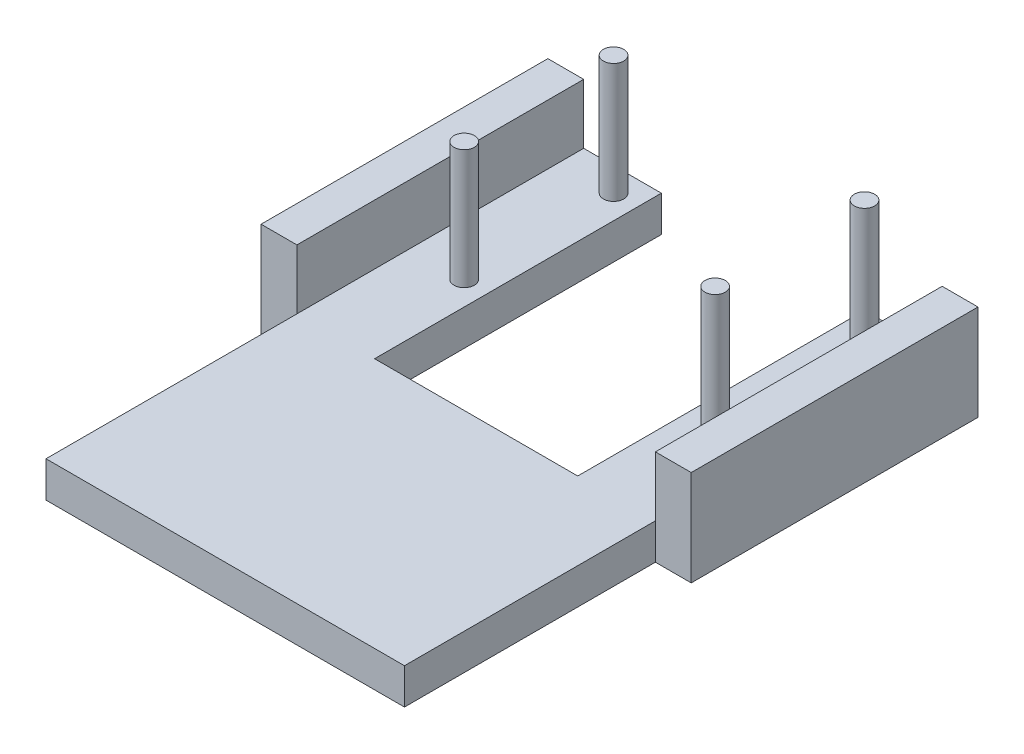
SolidWorks part; units mm, degrees
ref_plane "Front Plane" through (0, 0, 0) normal (0, 0, 1) x (1, 0, 0)
ref_plane "Top Plane" through (0, 0, 0) normal (0, 1, 0) x (1, 0, 0)
ref_plane "Right Plane" through (0, 0, 0) normal (1, 0, 0) x (0, 0, -1)
sketch "Sketch1" plane through (0, 0, 0) normal (0, 1, 0) x (1, 0, 0)
  line L0 (30, 0) -> (0, 0)
  line L17 (30, 0) -> (30, 21)
  line L18 (30, 21) -> (33, 21)
  line L19 (33, 21) -> (33, 45)
  line L20 (-3, 45) -> (6.5, 45)
  line L21 (-3, 45) -> (-3, 21)
  line L22 (-3, 21) -> (0, 21)
  line L23 (0, 21) -> (0, 0)
  line L24 (6.5, 45) -> (6.5, 21)
  line L25 (6.5, 21) -> (23.5, 21)
  line L26 (23.5, 21) -> (23.5, 45)
  line L27 (23.5, 45) -> (33, 45)
  dimension "D1" = 45
  dimension "D2" = 3
  dimension "D3" = 24
  dimension "D4" = 36
  dimension "D5" = 24
  dimension "D6" = 3
  dimension "D7" = 9.5
  dimension "D8" = 9.5
  dimension "D21" = 17
  dimension "D22" = 24
extrude "Boss-Extrude1" add sketch "Sketch1" along normal blind 3
sketch "Sketch2" plane through (0, 3, 0) normal (0, 1, 0) x (1, 0, 0)
  line L0 (0, 21) -> (0, 45)
  line L2 (0, 45) -> (-3, 45)
  line L3 (-3, 45) -> (-3, 21)
  line L4 (-3, 21) -> (0, 21)
  line L5 (33, 45) -> (30, 45)
  line L6 (33, 21) -> (33, 45)
  line L7 (30, 45) -> (30, 21)
  line L8 (30, 21) -> (33, 21)
  line L9 (4.5, 43) -> (25.5, 43) construction
  line L10 (6.5, 45) -> (-3, 45) construction
  line L11 (23.5, 21) -> (6.5, 21) construction
  line L12 (33, 45) -> (23.5, 45) construction
  circle A0 centre (4.5, 43) radius 0.85
  circle A1 centre (25.5, 43) radius 0.85
  circle A2 centre (25.5, 30.5) radius 0.85
  circle A3 centre (4.5, 30.5) radius 0.85
  point P26 (15, 43)
  point P32 (15, 21)
  dimension "D2" = 1.7
  dimension "D3" = 1.7
  dimension "D4" = 1.7
  dimension "D5" = 1.7
  dimension "D1" = 3
  dimension "D6" = 21
  dimension "D7" = 2
  dimension "D8" = 12.5
extrude "Boss-Extrude2" add sketch "Sketch2" along normal blind 5
sketch "Sketch3" plane through (0, 8, 0) normal (0, 1, 0) x (1, 0, 0)
  circle A0 centre (4.5, 43) radius 0.85
  circle A1 centre (25.5, 43) radius 0.85
  circle A2 centre (25.5, 30.5) radius 0.85
  circle A3 centre (4.5, 30.5) radius 0.85
  circle A6 centre (25.5, 30.5) radius 0.85 construction
  circle A7 centre (25.5, 43) radius 0.85 construction
  dimension "D1" = 1.7
  dimension "D2" = 1.7
  dimension "D3" = 1.7
  dimension "D4" = 1.7
extrude "Boss-Extrude3" add sketch "Sketch3" along normal blind 5
